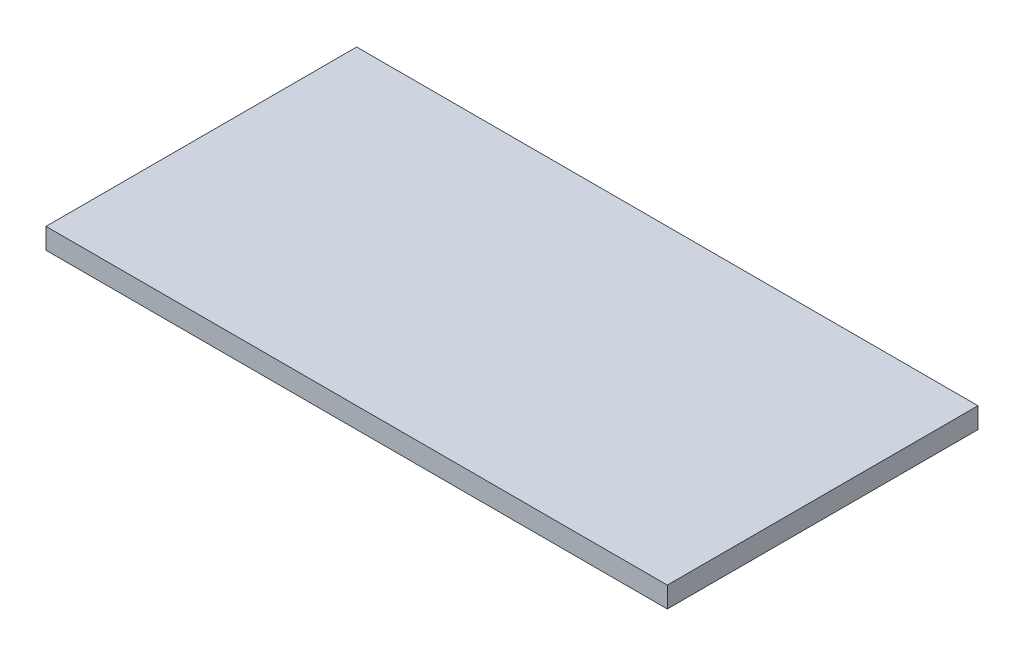
SolidWorks part; units mm, degrees
ref_plane "Front Plane" through (0, 0, 0) normal (0, 0, 1) x (1, 0, 0)
ref_plane "Top Plane" through (0, 0, 0) normal (0, 1, 0) x (1, 0, 0)
ref_plane "Right Plane" through (0, 0, 0) normal (1, 0, 0) x (0, 0, -1)
sketch "Sketch1" plane through (0, 0, 0) normal (0, 1, 0) x (1, 0, 0)
  line L1 (-8.2878, 3.8834) -> (21.7122, 3.8834)
  line L2 (-8.2878, 3.8834) -> (-8.2878, -11.1166)
  line L3 (-8.2878, -11.1166) -> (21.7122, -11.1166)
  line L4 (21.7122, 3.8834) -> (21.7122, -11.1166)
  dimension "D1" = 30
  dimension "D2" = 15
extrude "Boss-Extrude1" add sketch "Sketch1" along normal blind 1
